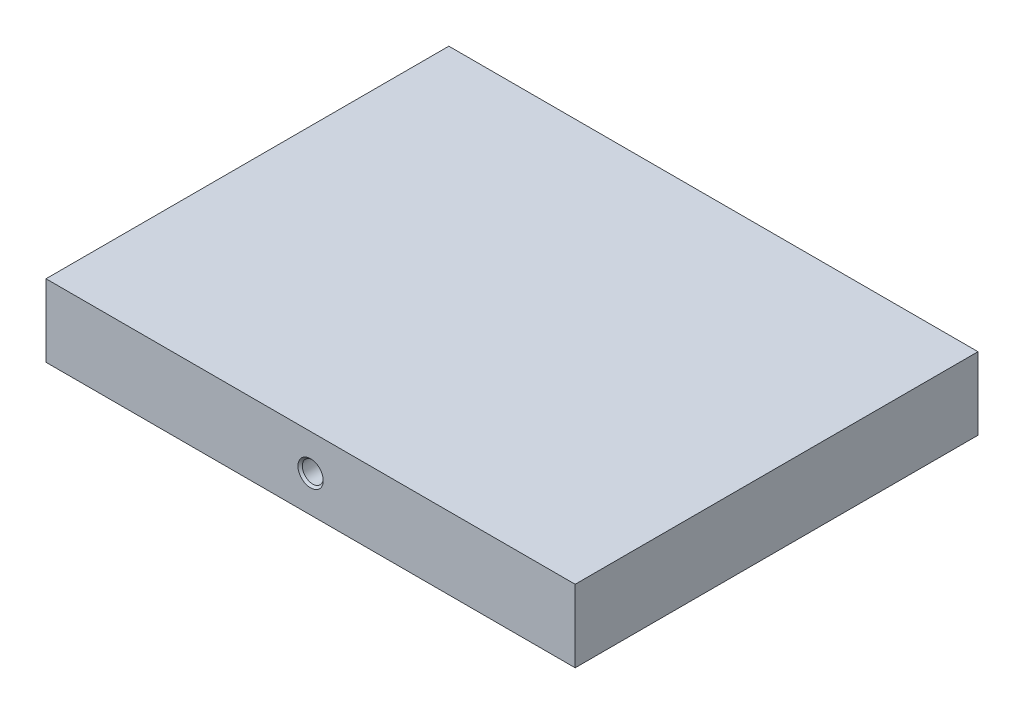
SolidWorks part; units mm, degrees
ref_plane "前视基准面" through (0, 0, 0) normal (0, 0, 1) x (1, 0, 0)
ref_plane "上视基准面" through (0, 0, 0) normal (0, 1, 0) x (1, 0, 0)
ref_plane "右视基准面" through (0, 0, 0) normal (1, 0, 0) x (0, 0, -1)
other "Configuration Table"
sketch "草图1" plane through (0, 0, 0) normal (0, 1, 0) x (1, 0, 0)
  line L1 (-63.25, -48.15) -> (63.25, -48.15)
  line L2 (-63.25, -48.15) -> (-63.25, 48.15)
  line L3 (-63.25, 48.15) -> (63.25, 48.15)
  line L4 (63.25, -48.15) -> (63.25, 48.15)
  line L5 (-63.25, -48.15) -> (63.25, 48.15) construction
  line L6 (-63.25, 48.15) -> (63.25, -48.15) construction
  point P0 (0, 0)
  dimension "D1" = 126.5
  dimension "D2" = 96.3
extrude "凸台-拉伸1" add sketch "草图1" along normal blind 17.3
sketch "草图2" plane through (0, 0, 48.15) normal (0, 0, 1) x (1, 0, 0)
  line L0 (-63.25, 8.65) -> (63.25, 8.65) construction
  line L1 (-63.25, 17.3) -> (-63.25, 0) construction
  line L2 (63.25, 17.3) -> (63.25, 0) construction
  point P7 (0, 8.65)
hole_wizard "M6 螺纹孔1" positions "草图2" profile "草图3" tap size "M6" standard "GB"
sketch "草图3" plane through (0, 8.65, 48.15) normal (1, 0, 0) x (0, -1, 0)
  line L0 (0, 0) -> (0, 9.5022)
  line L1 (0, 9.5022) -> (2.5, 8)
  line L2 (2.5, 8) -> (2.5, 0.525)
  line L3 (2.5, 0.525) -> (3.025, 0)
  line L5 (3.025, 0) -> (0, 0)
  line L6 (-2.5, 0.525) -> (-3.025, 0) construction
  line L10 (0, 9.5022) -> (-2.5, 8) construction
  line L11 (0, -6.35) -> (0, 107.95) construction
  dimension "螺纹孔钻头直径" = 5
  dimension "螺纹孔钻头深度" = 8
  dimension "近端锥形沉头孔直径" = 6.05
  dimension "近端锥形沉头孔角度" = 90
  dimension "导头角度" = 118
cosmetic thread "孔螺纹线1" parameters "D1"=5, "D2"=6
sketch "草图4" plane through (-63.25, 0, 0) normal (-1, 0, 0) x (0, 0, 1)
  line L0 (-48.15, 5.6) -> (48.15, 5.6) construction
  line L1 (-48.15, 17.3) -> (-48.15, 0) construction
  line L2 (48.15, 17.3) -> (48.15, 0) construction
  line L3 (-30.75, 5.6) -> (-19.25, 5.6) construction
  line L4 (-48.15, 0) -> (48.15, 0) construction
  circle A0 centre (-30.75, 5.6) radius 1.9
  circle A1 centre (-19.25, 5.6) radius 1.9
  circle A2 centre (-7.75, 5.6) radius 1.9
  circle A3 centre (3.75, 5.6) radius 1.9
  circle A4 centre (15.25, 5.6) radius 1.9
  dimension "D1" = 3.8
  dimension "D2" = 17.4
  dimension "D4" = 11.5
  dimension "D5" = 5.6
  dimension "D3" = 5
extrude "凸台-拉伸2" add sketch "草图4" along normal blind 1.2 separate body
sketch "草图5" plane through (-63.25, 0, 0) normal (-1, 0, 0) x (0, 0, 1)
  line L0 (-30.75, 5.6) -> (48.15, 5.6) construction
  line L1 (48.15, 17.3) -> (48.15, 0) construction
  line L3 (22.75, 7.35) -> (31.75, 7.35)
  line L4 (22.75, 7.35) -> (22.75, 3.85)
  line L5 (22.75, 3.85) -> (31.75, 3.85)
  line L6 (31.75, 7.35) -> (31.75, 3.85)
  line L7 (22.75, 7.35) -> (31.75, 3.85) construction
  line L8 (22.75, 3.85) -> (31.75, 7.35) construction
  circle A0 centre (15.25, 5.6) radius 1.9 construction
  point P5 (27.25, 5.6)
  dimension "D1" = 12
  dimension "D2" = 9
  dimension "D3" = 3.5
extrude "切除-拉伸1" cut sketch "草图5" against normal blind 5
sketch "草图6" plane through (0, 0, 0) normal (0, -1, 0) x (1, 0, 0)
  line L0 (-37.5, 0) -> (37.5, 0) construction
  point P1 (37.5, 0)
  point P2 (-37.5, 0)
  point P3 (0, 0)
  dimension "D1" = 75
hole_wizard "M4 螺纹孔1" positions "草图6" profile "草图7" tap size "M4" standard "GB"
sketch "草图7" plane through (37.5, 0, 0) normal (1, 0, 0) x (0, 0, -1)
  line L0 (0, 0) -> (0, 6.0914)
  line L1 (0, 6.0914) -> (1.65, 5.1)
  line L2 (1.65, 5.1) -> (1.65, 0.375)
  line L3 (1.65, 0.375) -> (2.025, 0)
  line L5 (2.025, 0) -> (0, 0)
  line L6 (-1.65, 0.375) -> (-2.025, 0) construction
  line L10 (0, 6.0914) -> (-1.65, 5.1) construction
  line L11 (0, -6.35) -> (0, 107.95) construction
  dimension "螺纹孔钻头直径" = 3.3
  dimension "螺纹孔钻头深度" = 5.1
  dimension "近端锥形沉头孔直径" = 4.05
  dimension "近端锥形沉头孔角度" = 90
  dimension "导头角度" = 118
cosmetic thread "孔螺纹线2" parameters "D1"=3, "D2"=4
cosmetic thread "孔螺纹线3" parameters "D1"=3, "D2"=4
